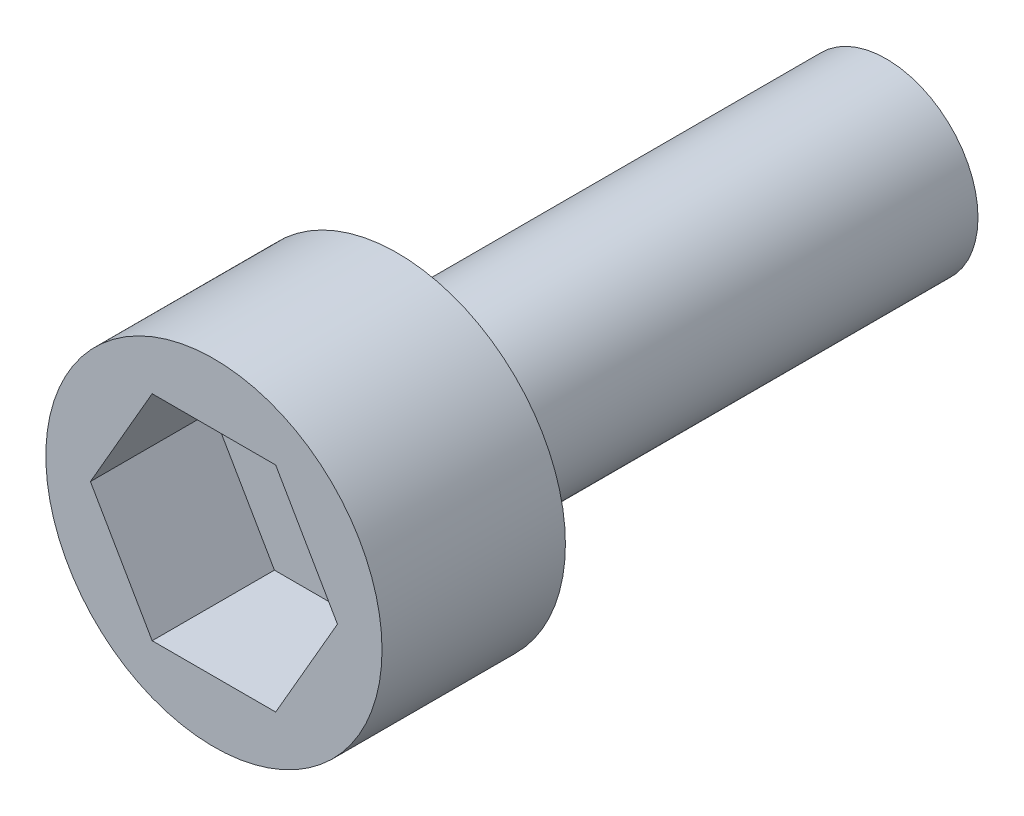
SolidWorks part; units mm, degrees
ref_plane "Plan de face" through (0, 0, 0) normal (0, 0, 1) x (1, 0, 0)
ref_plane "Plan de dessus" through (0, 0, 0) normal (0, 1, 0) x (1, 0, 0)
ref_plane "Plan de droite" through (0, 0, 0) normal (1, 0, 0) x (0, 0, -1)
sketch "Esquisse1" plane through (0, 0, 0) normal (0, 0, 1) x (1, 0, 0)
  circle A0 centre (0, 0) radius 1.5
  dimension "D1" = 3
extrude "Boss.-Extru.1" add sketch "Esquisse1" along normal blind 8
sketch "Esquisse2" plane through (0, 0, 8) normal (0, 0, 1) x (1, 0, 0)
  circle A0 centre (0, 0) radius 2.75
  dimension "D1" = 5.5
extrude "Boss.-Extru.2" add sketch "Esquisse2" along normal blind 3
sketch "Esquisse3" plane through (0, 0, 11) normal (0, 0, 1) x (1, 0, 0)
  line L1 (2.0207, 0) -> (1.0104, 1.75)
  line L2 (1.0104, 1.75) -> (-1.0104, 1.75)
  line L3 (-1.0104, 1.75) -> (-2.0207, 0)
  line L4 (-2.0207, 0) -> (-1.0104, -1.75)
  line L5 (-1.0104, -1.75) -> (1.0104, -1.75)
  line L6 (1.0104, -1.75) -> (2.0207, 0)
  circle A0 centre (0, 0) radius 1.75 construction
  dimension "D1" = 3.5
extrude "Enlèv. mat.-Extru.1" cut sketch "Esquisse3" against normal blind 2
